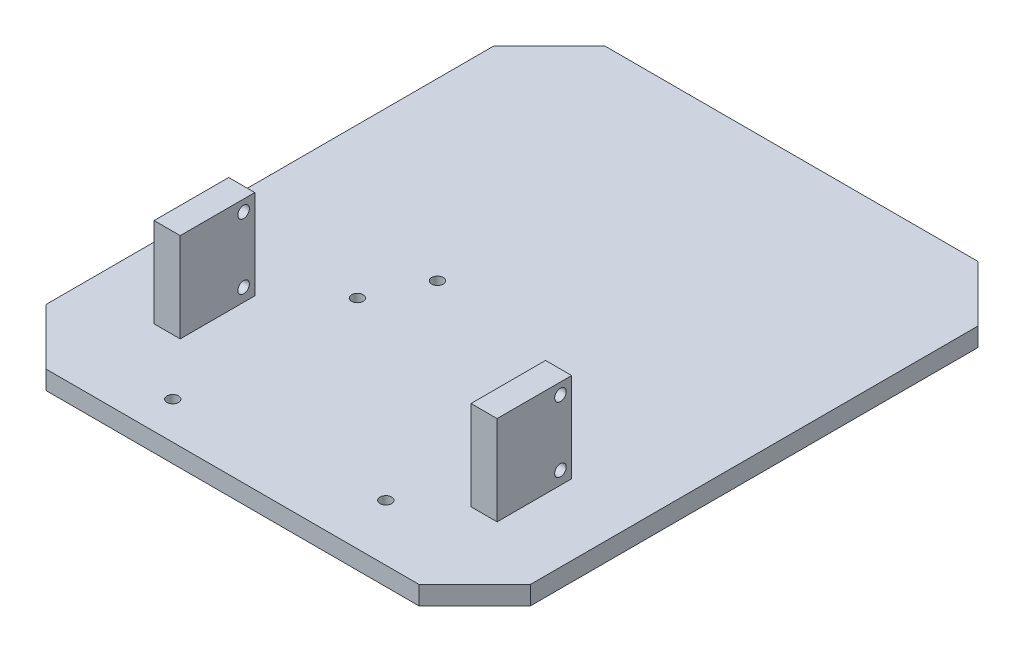
SolidWorks part; units mm, degrees
ref_plane "Front Plane" through (0, 0, 0) normal (0, 0, 1) x (1, 0, 0)
ref_plane "Top Plane" through (0, 0, 0) normal (0, 1, 0) x (1, 0, 0)
ref_plane "Right Plane" through (0, 0, 0) normal (1, 0, 0) x (0, 0, -1)
sketch "Sketch1" plane through (0, 0, 0) normal (0, 1, 0) x (1, 0, 0)
  line L1 (-65, 75) -> (65, 75)
  line L2 (-65, 75) -> (-65, -75)
  line L3 (-65, -75) -> (65, -75)
  line L4 (65, 75) -> (65, -75)
  line L5 (-65, 75) -> (65, -75) construction
  line L6 (-65, -75) -> (65, 75) construction
  point P0 (0, 0)
  dimension "D1" = 150
  dimension "D2" = 130
extrude "Boss-Extrude1" add sketch "Sketch1" along normal mid plane 5
sketch "Sketch4" plane through (0, 2.5, 0) normal (0, 1, 0) x (1, 0, 0)
  line L0 (-65, -75) -> (65, -75) construction
  line L1 (-65, 75) -> (-65, -75) construction
  line L5 (-65, 75) -> (-65, -75) construction
  circle A0 centre (-24.73, -16.74) radius 1.55
  circle A1 centre (26.07, -31.98) radius 1.55
  circle A2 centre (-26, -65) radius 1.55
  circle A3 centre (26.07, -59.92) radius 1.55
  circle A4 centre (-18, -2) radius 1.55
  point P16 (0, -75)
  dimension "D1" = 3.1
  dimension "D9" = 3.1
  dimension "D2" = 48.26
  dimension "D3" = 1.27
  dimension "D4" = 15.24
  dimension "D5" = 50.8
  dimension "D6" = 27.94
  dimension "D7" = 10
  dimension "D8" = 39
  dimension "D10" = 47
  dimension "D11" = 73
extrude "Cut-Extrude2" cut sketch "Sketch4" against normal up to surface (5 mm away) up to face at (0, -2.5, 0)
sketch "Sketch5" plane through (0, 2.5, 0) normal (0, 1, 0) x (1, 0, 0)
  line L0 (-65, 75) -> (-65, -75) construction
  line L1 (-46, -30) -> (-39, -30)
  line L2 (-46, -30) -> (-46, -50)
  line L3 (-46, -50) -> (-39, -50)
  line L4 (-39, -30) -> (-39, -50)
  line L5 (39, -30) -> (46, -30)
  line L6 (39, -30) -> (39, -50)
  line L7 (39, -50) -> (46, -50)
  line L8 (46, -30) -> (46, -50)
  line L9 (65, -75) -> (65, 75) construction
  line L10 (-65, -75) -> (65, -75) construction
  dimension "D1" = 19
  dimension "D2" = 19
  dimension "D3" = 7
  dimension "D4" = 20
  dimension "D5" = 25
  dimension "D6" = 25
extrude "Boss-Extrude3" add sketch "Sketch5" along normal blind 24
sketch "Sketch6" plane through (-46, 0, 0) normal (-1, 0, 0) x (0, 0, 1)
  line L0 (30, 26.5) -> (50, 26.5) construction
  line L2 (30, 26.5) -> (30, 2.5) construction
  circle A0 centre (33, 23.5) radius 1.55
  circle A1 centre (33, 6) radius 1.55
  point P4 (0, 0)
  point P5 (28.396, 5.8854)
  dimension "D1" = 3.1
  dimension "D2" = 17.5
  dimension "D3" = 3
  dimension "D4" = 3
extrude "Cut-Extrude3" cut sketch "Sketch6" against normal up to surface (92 mm away) up to face at (46, 14.5, 40)
sketch "Sketch7" plane through (0, 2.5, 0) normal (0, 1, 0) x (1, 0, 0)
  line L0 (-65, -75) -> (-65, -60)
  line L1 (-65, 75) -> (-65, -75) construction
  line L2 (-65, -60) -> (-50, -75)
  line L3 (-65, -75) -> (65, -75) construction
  line L4 (-50, -75) -> (-65, -75)
  line L5 (65, -75) -> (65, -60)
  line L6 (65, -75) -> (65, 75) construction
  line L7 (65, -60) -> (50, -75)
  line L8 (50, -75) -> (65, -75)
  line L9 (-65, 75) -> (-65, 60)
  line L10 (-65, 60) -> (-50, 75)
  line L11 (65, 75) -> (-65, 75) construction
  line L12 (-50, 75) -> (-65, 75)
  line L13 (65, 75) -> (65, 60)
  line L14 (65, 60) -> (50, 75)
  line L15 (50, 75) -> (65, 75)
  dimension "D1" = 15
  dimension "D2" = 15
extrude "Cut-Extrude4" cut sketch "Sketch7" against normal up to surface (5 mm away) up to face at (-18, -2.5, 3.55)
